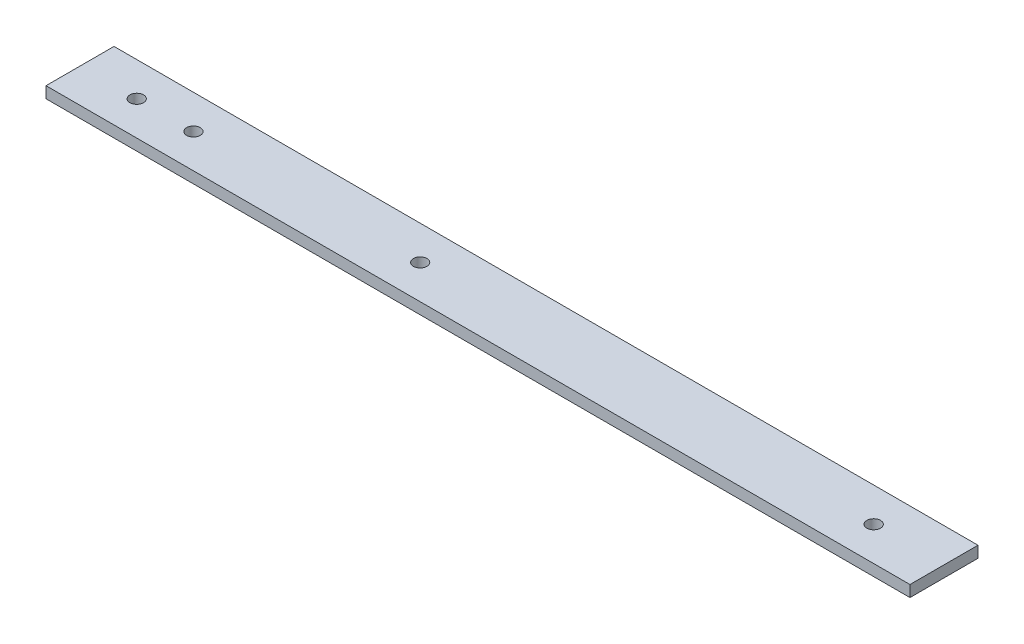
SolidWorks part; units mm, degrees
ref_plane "Front Plane" through (0, 0, 0) normal (0, 0, 1) x (1, 0, 0)
ref_plane "Top Plane" through (0, 0, 0) normal (0, 1, 0) x (1, 0, 0)
ref_plane "Right Plane" through (0, 0, 0) normal (1, 0, 0) x (0, 0, -1)
sketch "Sketch1" plane through (0, 0, 0) normal (0, 1, 0) x (1, 0, 0)
  line L1 (0, 0) -> (381, 0)
  line L2 (0, 0) -> (0, 30)
  line L3 (0, 30) -> (381, 30)
  line L4 (381, 0) -> (381, 30)
  circle A0 centre (25, 15) radius 3
  circle A1 centre (50, 15) radius 3
  circle A2 centre (150, 15) radius 3
  circle A3 centre (350, 15) radius 3
  dimension "D3" = 6
  dimension "D4" = 6
  dimension "D5" = 6
  dimension "D6" = 6
  dimension "D1" = 30
  dimension "D2" = 381
  dimension "D7" = 25
  dimension "D8" = 25
  dimension "D9" = 100
  dimension "D10" = 200
extrude "Boss-Extrude1" add sketch "Sketch1" along normal blind 5
